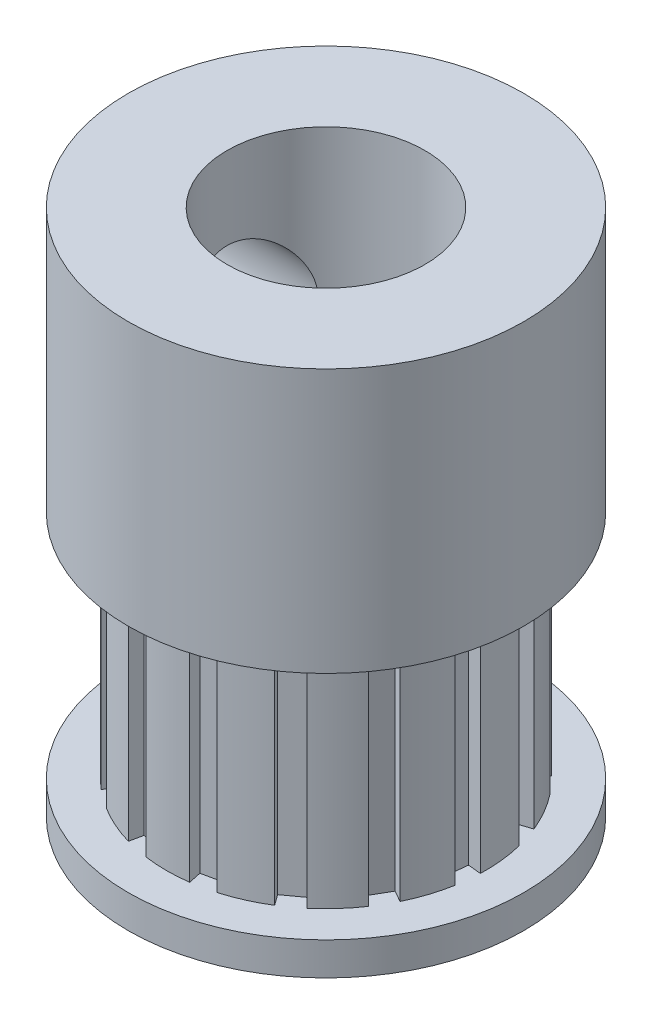
SolidWorks part; units mm, degrees
ref_plane "前视" through (0, 0, 0) normal (0, 0, 1) x (1, 0, 0)
ref_plane "上视" through (0, 0, 0) normal (0, 1, 0) x (1, 0, 0)
ref_plane "右视" through (0, 0, 0) normal (1, 0, 0) x (0, 0, -1)
sketch "草图1" plane through (0, 0, 0) normal (0, 1, 0) x (1, 0, 0)
  circle A0 centre (0, 0) radius 6
  dimension "D1" = 12
extrude "凸台-拉伸1" add sketch "草图1" along normal blind 1
sketch "草图2" plane through (0, 1, 0) normal (0, 1, 0) x (1, 0, 0)
  line L0 (-0.35, 4.8273) -> (-0.35, 4.4273)
  line L1 (0.35, 4.8273) -> (0.35, 4.4273)
  line L2 (0.35, 4.4273) -> (-0.35, 4.4273)
  line L3 (1.6437, 4.5523) -> (1.481, 4.1869)
  line L4 (2.1205, 3.9022) -> (1.481, 4.1869)
  line L5 (2.2832, 4.2676) -> (2.1205, 3.9022)
  line L6 (3.3532, 3.4902) -> (3.056, 3.2226)
  line L7 (3.5243, 2.7024) -> (3.056, 3.2226)
  line L8 (3.8216, 2.97) -> (3.5243, 2.7024)
  line L9 (4.4829, 1.8246) -> (4.1025, 1.701)
  line L10 (4.3188, 1.0352) -> (4.1025, 1.701)
  line L11 (4.6992, 1.1589) -> (4.3188, 1.0352)
  line L12 (4.8375, -0.1565) -> (4.4397, -0.1147)
  line L13 (4.3665, -0.8109) -> (4.4397, -0.1147)
  line L14 (4.7643, -0.8527) -> (4.3665, -0.8109)
  line L15 (4.3556, -2.1106) -> (4.0092, -1.9106)
  line L16 (3.6592, -2.5168) -> (4.0092, -1.9106)
  line L17 (4.0056, -2.7168) -> (3.6592, -2.5168)
  line L18 (3.1206, -3.6997) -> (2.8855, -3.3761)
  line L19 (2.3192, -3.7875) -> (2.8855, -3.3761)
  line L20 (2.5543, -4.1111) -> (2.3192, -3.7875)
  line L21 (1.346, -4.6491) -> (1.2628, -4.2578)
  line L22 (0.5781, -4.4033) -> (1.2628, -4.2578)
  line L23 (0.6613, -4.7946) -> (0.5781, -4.4033)
  line L24 (-0.6613, -4.7946) -> (-0.5781, -4.4033)
  line L25 (-1.2628, -4.2578) -> (-0.5781, -4.4033)
  line L26 (-1.346, -4.6491) -> (-1.2628, -4.2578)
  line L27 (-2.5543, -4.1111) -> (-2.3192, -3.7875)
  line L28 (-2.8855, -3.3761) -> (-2.3192, -3.7875)
  line L29 (-3.1206, -3.6997) -> (-2.8855, -3.3761)
  line L30 (-4.0056, -2.7168) -> (-3.6592, -2.5168)
  line L31 (-4.0092, -1.9106) -> (-3.6592, -2.5168)
  line L32 (-4.3556, -2.1106) -> (-4.0092, -1.9106)
  line L33 (-4.7643, -0.8527) -> (-4.3665, -0.8109)
  line L34 (-4.4397, -0.1147) -> (-4.3665, -0.8109)
  line L35 (-4.8375, -0.1565) -> (-4.4397, -0.1147)
  line L36 (-4.6992, 1.1589) -> (-4.3188, 1.0352)
  line L37 (-4.1025, 1.701) -> (-4.3188, 1.0352)
  line L38 (-4.4829, 1.8246) -> (-4.1025, 1.701)
  line L39 (-3.8216, 2.97) -> (-3.5243, 2.7024)
  line L40 (-3.056, 3.2226) -> (-3.5243, 2.7024)
  line L41 (-3.3532, 3.4902) -> (-3.056, 3.2226)
  line L42 (-2.2832, 4.2676) -> (-2.1205, 3.9022)
  line L43 (-1.481, 4.1869) -> (-2.1205, 3.9022)
  line L44 (-1.6437, 4.5523) -> (-1.481, 4.1869)
  line L60 (-6, 0) -> (6, 0) construction
  circle A0 centre (0, 0) radius 4.84
  circle A1 centre (0, 0) radius 6 construction
  point P85 (0, 0)
  dimension "D1" = 9.68
  dimension "D2" = 0.35
  dimension "D3" = 0.7
  dimension "D4" = 0.4
  dimension "D5" = 15
extrude "凸台-拉伸2" add sketch "草图2" along normal blind 7
sketch "草图3" plane through (0, 8, 0) normal (0, 1, 0) x (1, 0, 0)
  circle A0 centre (0, 0) radius 6
  dimension "D1" = 12
extrude "凸台-拉伸3" add sketch "草图3" along normal blind 8
sketch "草图4" plane through (0, 16, 0) normal (0, 1, 0) x (1, 0, 0)
  circle A0 centre (0, 0) radius 3
  dimension "D1" = 6
extrude "切除-拉伸1" cut sketch "草图4" against normal up to next
sketch "草图5" plane through (0, 0, 0) normal (1, 0, 0) x (0, 0, -1)
  line L0 (6, 16) -> (-6, 16) construction
  circle A0 centre (0, 11.5) radius 2
  dimension "D1" = 4
  dimension "D2" = 4.5
extrude "切除-拉伸2" cut sketch "草图5" against normal up to next contours A0
cosmetic thread "装饰螺纹线1" parameters "D2"=4.5
